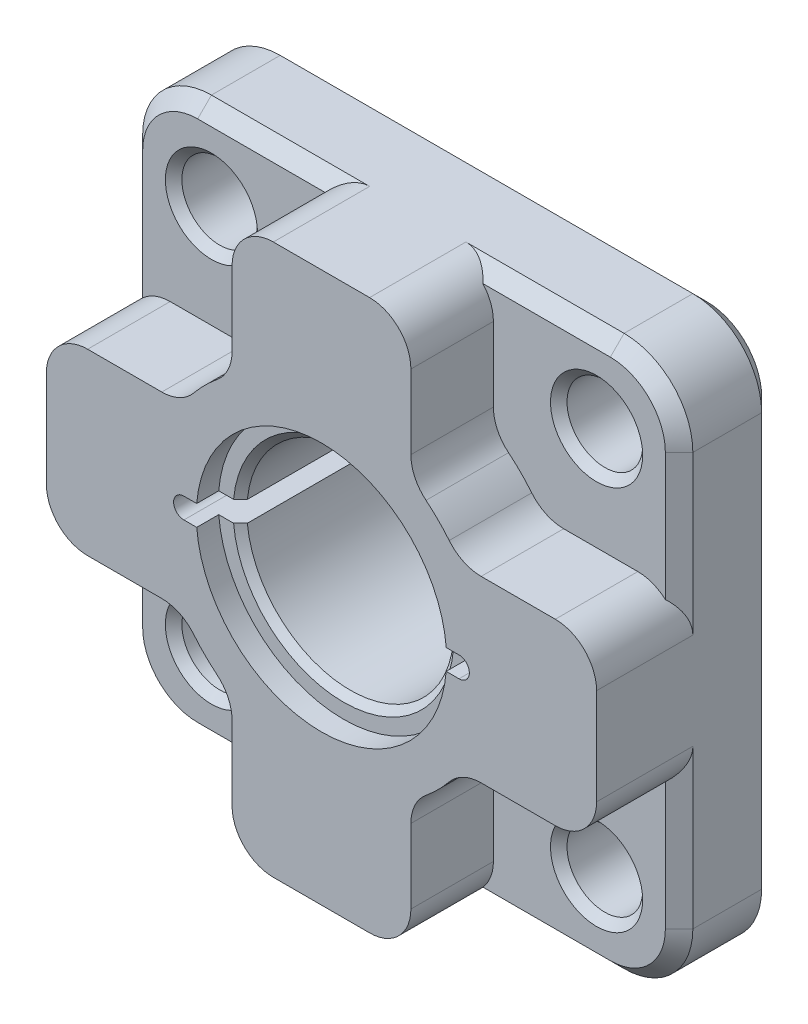
SolidWorks part; units mm, degrees
material "ABS"
ref_plane "Płaszczyzna przednia" through (0, 0, 0) normal (0, 0, 1) x (1, 0, 0)
ref_plane "Płaszczyzna górna" through (0, 0, 0) normal (0, 1, 0) x (1, 0, 0)
ref_plane "Płaszczyzna prawa" through (0, 0, 0) normal (1, 0, 0) x (0, 0, -1)
sketch "Szkic1" plane through (0, 0, 0) normal (0, 0, 1) x (1, 0, 0)
  line L1 (-20, 20) -> (20, 20)
  line L2 (-20, 20) -> (-20, -20)
  line L3 (-20, -20) -> (20, -20)
  line L4 (20, 20) -> (20, -20)
  line L5 (-20, 20) -> (20, -20) construction
  line L6 (-20, -20) -> (20, 20) construction
  point P0 (0, 0)
  dimension "D1" = 40
extrude "Dodanie-wyciągnięcie1" add sketch "Szkic1" along normal blind 13
hole_wizard "Otwór pod śrubę M51" positions "Szkic2" profile "Szkic3" hole size "M5" standard "ISO" end condition through all
sketch "Szkic2" plane through (0, 0, 13) normal (0, 0, 1) x (1, 0, 0)
  line L0 (0, 0) -> (0, 50000) construction
  line L1 (0, 0) -> (50000, 0) construction
  point P0 (-14, 14)
  point P10 (14, 14)
  point P12 (14, -14)
  point P13 (-14, -14)
  dimension "D1" = 28
  dimension "D2" = 28
sketch "Szkic3" plane through (-14, 14, 13) normal (1, 0, 0) x (0, -1, 0)
  line L0 (0, 0) -> (0, 13)
  line L1 (0, 13) -> (2.75, 13)
  line L2 (2.75, 13) -> (2.75, 0)
  line L5 (2.75, 0) -> (0, 0)
  line L11 (0, -6.35) -> (0, 107.95) construction
  dimension "Średnica otworu na wylot" = 5.5
  dimension "Głębokość otworu na wylot" = 13
sketch "Szkic4" plane through (0, 0, 13) normal (0, 0, 1) x (1, 0, 0)
  line L0 (-10, 0) -> (10, 0) construction
  line L1 (-10, 0.75) -> (10, 0.75)
  line L2 (-10, -0.75) -> (10, -0.75)
  circle A0 centre (0, 0) radius 6.05
  arc A1 (-10, 0.75) -> (-10, -0.75) centre (-10, 0) ccw
  arc A2 (10, -0.75) -> (10, 0.75) centre (10, 0) ccw
  point P5 (0, 0)
  dimension "D1" = 12.1
  dimension "D2" = 1.5
  dimension "D3" = 20
extrude "Wytnij-wyciągnięcie1" cut sketch "Szkic4" against normal through all
sketch "Szkic5" plane through (0, 0, 13) normal (0, 0, 1) x (1, 0, 0)
  line L0 (6.5, 10.0871) -> (6.5, 20)
  line L1 (20, 20) -> (-20, 20) construction
  line L2 (20, 6.5) -> (10.0871, 6.5)
  line L3 (20, -20) -> (20, 20) construction
  line L4 (6.5, 20) -> (20, 20)
  line L5 (20, 20) -> (20, 6.5)
  circle A0 centre (0, 0) radius 12
  circle A1 centre (14, 14) radius 7.5 construction
  circle M14 centre (14, 14) radius 2.75
  line M17 (20, -20) -> (20, 20)
  line M18 (20, 20) -> (-20, 20)
  dimension "D1" = 24
  dimension "D2" = 15
extrude "Wytnij-wyciągnięcie2" cut sketch "Szkic5" against normal offset from surface (6 mm away) 7 contours A0 L2 L0 M17 M18 M14 up to face at (0, 0, 0)
pattern_circular "Szyk kołowy1" count 4 over 360 about axis through (0, 0, 0) along (0, 0, 1) of "Wytnij-wyciągnięcie2"
fillet "Zaokrąglenie1" radius 5 4 edges at (-20, 20, 3.5) (-20, -20, 3.5) (20, -20, 3.5) (20, 20, 3.5)
fillet "Zaokrąglenie2" radius 3 16 edges at (-6.5, -20, 10) (-6.5, -10.0871, 10) (-10.0871, -6.5, 10) (-20, -6.5, 10) (6.5, -20, 10) (6.5, -10.0871, 10) (10.0871, -6.5, 10) (20, -6.5, 10) (20, 6.5, 10) (10.0871, 6.5, 10) (6.5, 10.0871, 10) (6.5, 20, 10) (-6.5, 20, 10) (-6.5, 10.0871, 10) (-10.0871, 6.5, 10) (-20, 6.5, 10)
chamfer "Sfazowanie2" distance 1 angle 45 20 edges at (0, -20, 0) (18.5355, -18.5355, 0) (-18.5355, -18.5355, 0) (20, 0, 0) (-20, 0, 0) (18.5355, 18.5355, 0) (-18.5355, 18.5355, 0) (0, 20, 0) (-20, -9.25, 7) (-9.25, -20, 7) (-18.5355, -18.5355, 7) (9.25, -20, 7) (18.5355, -18.5355, 7) (20, -9.25, 7) (-20, 9.25, 7) (-18.5355, 18.5355, 7) (-9.25, 20, 7) (20, 9.25, 7) (9.25, 20, 7) (18.5355, 18.5355, 7)
chamfer "Sfazowanie3" distance 0.6 angle 45 8 edges at (16.75, -14, 7) (16.75, -14, 0) (-11.25, -14, 0) (-11.25, -14, 7) (-11.25, 14, 7) (-11.25, 14, 0) (16.75, 14, 0) (16.75, 14, 7)
sketch "Szkic6" plane through (0, 0, 0) normal (1, 0, 0) x (0, 0, -1)
  line L0 (-13, 9.1) -> (-11.4, 9.1)
  line L1 (-13, 9.2865) -> (-13, 7.6) construction
  line L2 (-11.4, 9.1) -> (-11.4, 7.525)
  line L3 (-11.4, 7.525) -> (0, 7.525)
  line L4 (0, 7.525) -> (0, 0)
  line L5 (0, 0) -> (-13, 0)
  line L6 (-13, 0) -> (-13, 9.1)
  line L7 (0, 0) -> (50000, 0) construction
  line L8 (0, 15) -> (0, -15) construction
  line L9 (-13, 6.5) -> (-13, 3.5) construction
  point P13 (0, 0)
  dimension "D1" = 15.05
  dimension "D2" = 18.2
  dimension "D3" = 1.6
revolve "Wycięcie-obrót1" cut sketch "Szkic6" angle 360 about L7
chamfer "Sfazowanie4" distance 0.5 angle 45 4 edges at (0, -7.525, 0) (0, 7.525, 0) (0, -7.525, 11.4) (0, 7.525, 11.4)
equation "\"Powierzchnia zewnętrzna\"= \"SW-Obszar powierzchni\" / 1e6"
